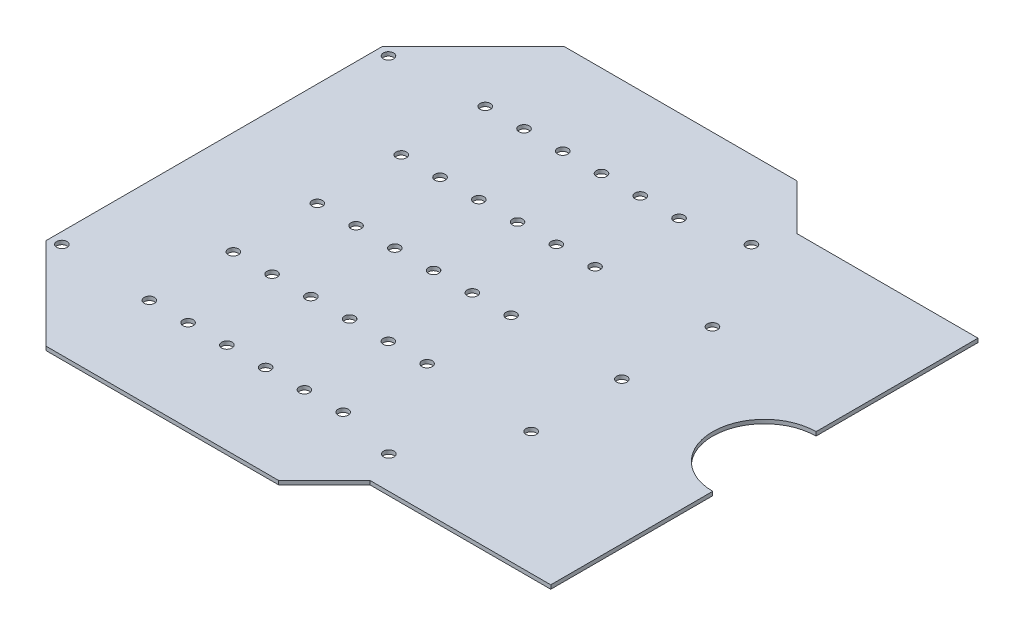
SolidWorks part; units mm, degrees
ref_plane "Ön Düzlem" through (0, 0, 0) normal (0, 0, 1) x (1, 0, 0)
ref_plane "Üst Düzlem" through (0, 0, 0) normal (0, 1, 0) x (1, 0, 0)
ref_plane "Sağ Düzlem" through (0, 0, 0) normal (1, 0, 0) x (0, 0, -1)
sketch "Çizim1" plane through (0, 0, 0) normal (0, 1, 0) x (1, 0, 0)
  line L0 (-27.7848, -18.8179) -> (-27.7848, 111.1821)
  line L1 (-27.7848, 111.1821) -> (7.5705, 146.5374)
  line L2 (7.5705, 146.5374) -> (97.5705, 146.5374)
  line L3 (97.5705, 146.5374) -> (115.2482, 128.8598)
  line L4 (115.2482, 128.8598) -> (185.2482, 128.8598)
  line L5 (-27.7848, -18.8179) -> (7.5705, -54.1732)
  line L6 (7.5705, -54.1732) -> (97.5705, -54.1732)
  line L7 (97.5705, -54.1732) -> (115.2482, -36.4956)
  line L8 (115.2482, -36.4956) -> (185.2482, -36.4956)
  line L9 (185.2482, -36.4956) -> (185.2482, 128.8598)
  dimension "D1" = 165.3553
  dimension "D2" = 70
  dimension "D3" = 25
  dimension "D4" = 90
  dimension "D5" = 50
  dimension "D6" = 130
extrude "Yükseklik-Ekstrüzyon1" add sketch "Çizim1" along normal blind 1.5
sketch "Çizim2" plane through (0, 1.5, 0) normal (0, 1, 0) x (1, 0, 0)
  circle A0 centre (-23.4334, 109.3797) radius 2
  circle A1 centre (-23.4334, -17.0155) radius 2
  circle A2 centre (110.0705, -23.9955) radius 2
  circle A3 centre (110.0705, 116.3597) radius 2
  circle A12 centre (130.0705, 46.1821) radius 2
  circle A13 centre (130.0705, 81.2709) radius 2
  circle A14 centre (130.0705, 11.0933) radius 2
extrude "Kes-Ekstrüzyon1" cut sketch "Çizim2" against normal blind 10
sketch "Çizim3" plane through (0, 1.5, 0) normal (0, 1, 0) x (1, 0, 0)
  circle A0 centre (12.2152, 46.1821) radius 2
  circle A1 centre (12.2152, 78.6821) radius 2
  circle A2 centre (12.2152, 13.6821) radius 2
  circle A3 centre (27.2152, 78.6821) radius 2
  circle A4 centre (42.2152, 78.6821) radius 2
  circle A5 centre (57.2152, 78.6821) radius 2
  circle A6 centre (72.2152, 78.6821) radius 2
  circle A7 centre (87.2152, 78.6821) radius 2
  circle A8 centre (27.2152, 46.1821) radius 2
  circle A9 centre (42.2152, 46.1821) radius 2
  circle A10 centre (57.2152, 46.1821) radius 2
  circle A11 centre (72.2152, 46.1821) radius 2
  circle A12 centre (87.2152, 46.1821) radius 2
  circle A13 centre (27.2152, 13.6821) radius 2
  circle A14 centre (42.2152, 13.6821) radius 2
  circle A15 centre (57.2152, 13.6821) radius 2
  circle A16 centre (72.2152, 13.6821) radius 2
  circle A17 centre (87.2152, 13.6821) radius 2
  circle A18 centre (12.2152, -18.8179) radius 2
  circle A19 centre (12.2152, 111.1821) radius 2
  circle A20 centre (27.2152, 111.1821) radius 2
  circle A21 centre (42.2152, 111.1821) radius 2
  circle A22 centre (57.2152, 111.1821) radius 2
  circle A23 centre (72.2152, 111.1821) radius 2
  circle A24 centre (87.2152, 111.1821) radius 2
  circle A25 centre (27.2152, -18.8179) radius 2
  circle A26 centre (42.2152, -18.8179) radius 2
  circle A27 centre (57.2152, -18.8179) radius 2
  circle A28 centre (72.2152, -18.8179) radius 2
  circle A29 centre (87.2152, -18.8179) radius 2
  dimension "D1" = 6
  dimension "D4" = 4
  dimension "D2" = 6
  dimension "D3" = 6
  dimension "D5" = 6
  dimension "D6" = 6
extrude "Kes-Ekstrüzyon2" cut sketch "Çizim3" against normal blind 10
sketch "Çizim4" plane through (0, 1.5, 0) normal (0, 1, 0) x (1, 0, 0)
  line L0 (185.2482, -36.4956) -> (185.2482, 128.8598) construction
  circle A0 centre (185.2482, 46.1821) radius 20
extrude "Kes-Ekstrüzyon3" cut sketch "Çizim4" against normal blind 10
